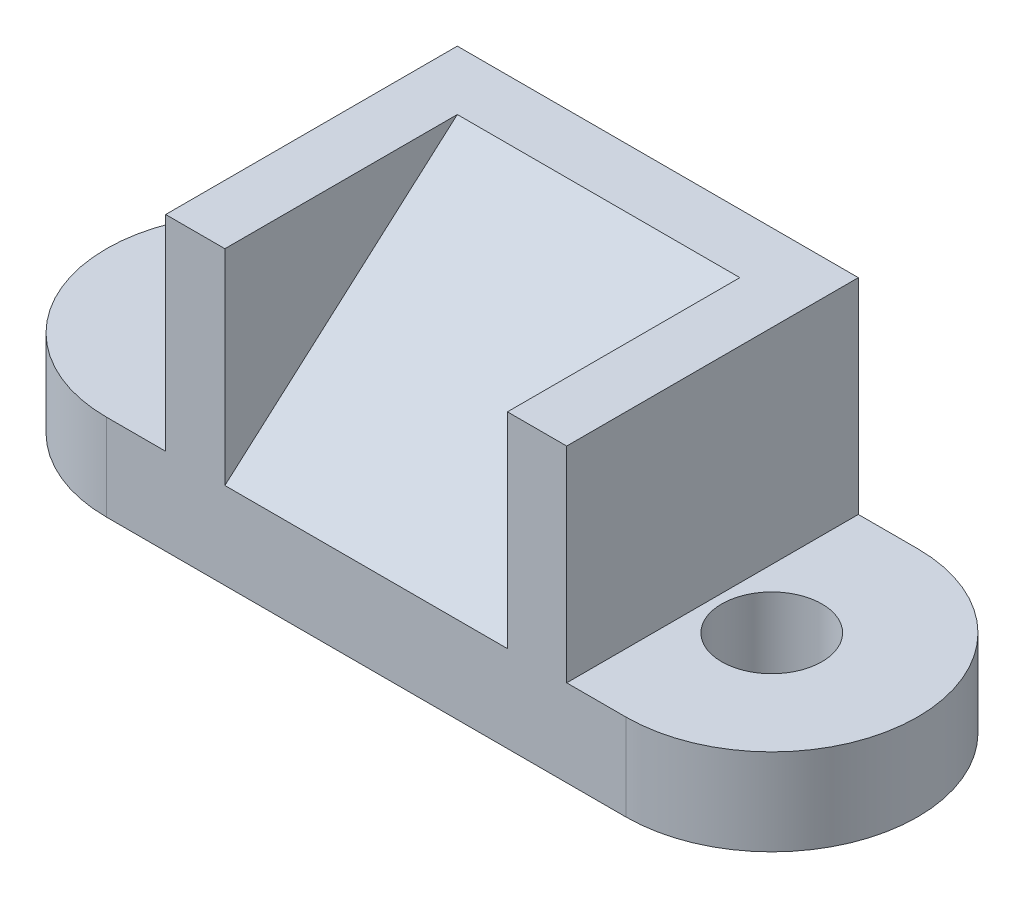
SolidWorks part; units mm, degrees
ref_plane "Front Plane" through (0, 0, 0) normal (0, 0, 1) x (1, 0, 0)
ref_plane "Top Plane" through (0, 0, 0) normal (0, 1, 0) x (1, 0, 0)
ref_plane "Right Plane" through (0, 0, 0) normal (1, 0, 0) x (0, 0, -1)
sketch "Sketch1" plane through (0, 0, 0) normal (0, 1, 0) x (1, 0, 0)
  line L2 (0, 0) -> (114, 0) construction
  line L3 (57, 0) -> (57, 46.98) construction
  line L4 (57, 0) -> (57, -55.98) construction
  line L7 (0, -32) -> (114, -32)
  line L8 (0, 32) -> (114, 32)
  arc A0 (0, 32) -> (0, -32) centre (0, 0) ccw
  arc A3 (114, 32) -> (114, -32) centre (114, 0) cw
  dimension "D1" = 64
  dimension "D3" = 114
extrude "Boss-Extrude2" add sketch "Sketch1" along normal blind 64
sketch "Sketch6" plane through (0, 64, 0) normal (0, 1, 0) x (1, 0, 0)
  line L5 (57, 46.98) -> (57, -55.98)
  line L7 (114, 32) -> (114, -32)
  line L8 (15.6619, 32) -> (93.8953, 32)
  line L9 (0, 32) -> (114, 32) construction
  line L10 (93.8953, 32) -> (93.8953, -32)
  line L11 (0, -32) -> (114, -32) construction
  line L12 (93.8953, -32) -> (15.6619, -32)
  line L13 (15.6619, -32) -> (15.6619, 32)
  line L14 (0, 32) -> (0, -32)
  circle A1 centre (0, 0) radius 11
  circle A6 centre (114, 0) radius 11
  arc A7 (0, 32) -> (0, -32) centre (0, 0) ccw
  arc A8 (0, 32) -> (0, -32) centre (0, 0) ccw construction
  arc A9 (114, -32) -> (114, 32) centre (114, 0) ccw
  arc A10 (114, -32) -> (114, 32) centre (114, 0) ccw construction
  dimension "D1" = 22
  dimension "D2" = 22
extrude "Cut-Extrude3" cut sketch "Sketch6" against normal blind 45 contours L14 A7
sketch "Sketch7" plane through (0, 64, 0) normal (0, 1, 0) x (1, 0, 0)
  circle A0 centre (0, 0) radius 11
  dimension "D1" = 22
extrude "Cut-Extrude5" cut sketch "Sketch7" against normal blind 96
sketch "Sketch8" plane through (0, 64, 0) normal (0, 1, 0) x (1, 0, 0)
  circle A0 centre (114, 0) radius 11
  dimension "D1" = 22
extrude "Cut-Extrude6" cut sketch "Sketch8" against normal blind 105
sketch "Sketch9" plane through (0, 64, 0) normal (0, 1, 0) x (1, 0, 0)
  line L0 (114, 32) -> (114, -32)
  arc A0 (114, -32) -> (114, 32) centre (114, 0) ccw
  arc A1 (114, -32) -> (114, 32) centre (114, 0) ccw construction
extrude "Cut-Extrude7" cut sketch "Sketch9" against normal blind 45
sketch "Sketch10" plane through (0, 64, 0) normal (0, 1, 0) x (1, 0, 0)
  line L0 (0, 32) -> (13, 32)
  line L1 (0, 32) -> (114, 32) construction
  line L2 (13, 32) -> (13, -32)
  line L3 (0, -32) -> (114, -32) construction
  line L8 (0, 32) -> (0, -32)
  line L9 (0, -32) -> (13, -32)
  dimension "D1" = 13
extrude "Cut-Extrude8" cut sketch "Sketch10" against normal blind 45
sketch "Sketch11" plane through (0, 64, 0) normal (0, 1, 0) x (1, 0, 0)
  line L0 (114, 32) -> (101, 32)
  line L1 (0, 32) -> (114, 32) construction
  line L2 (101, 32) -> (101, -32)
  line L3 (0, -32) -> (114, -32) construction
  line L4 (101, -32) -> (114, -32)
  line L5 (114, 32) -> (114, -32)
  dimension "D1" = 13
extrude "Cut-Extrude9" cut sketch "Sketch11" against normal blind 45 contours L5 L4 L2 L0
sketch "Sketch12" plane through (0, 64, 0) normal (0, 1, 0) x (1, 0, 0)
  line L0 (13, -32) -> (26, -32)
  line L2 (88, -32) -> (101, -32)
  line L3 (101, 32) -> (101, -32)
  line L4 (13, 32) -> (13, -32)
  line L5 (88, 19) -> (88, -32)
  line L6 (0, -32) -> (114, -32) construction
  line L7 (88, -32) -> (26, -32)
  line L8 (26, -32) -> (26, 19)
  line L9 (88, -32) -> (101, -32)
  line L10 (13, -32) -> (26, -32)
  line L11 (26, 19) -> (88, 19)
  line L12 (13, 32) -> (101, 32)
  line L13 (26, -32) -> (88, -32)
  dimension "D1" = 13
  dimension "D2" = 13
  dimension "D3" = 13
sketch "Sketch13" plane through (101, 0, 0) normal (1, 0, 0) x (0, 0, -1)
  line L0 (19, 64) -> (-32, 19)
  line L1 (-32, 64) -> (19, 64) construction
  line L2 (-32, 19) -> (-32, 64)
  line L3 (-32, 64) -> (19, 64)
sketch "Sketch14" plane through (0, 0, 32) normal (0, 0, 1) x (1, 0, 0)
  line L3 (26, 64) -> (26, 19)
  line L4 (13, 64) -> (26, 64) construction
  line L5 (87.8632, 64) -> (87.8632, 19)
  line L7 (87.8632, 19) -> (26, 19)
ref_plane "Plane1" through (57, 0, 0) normal (-1, 0, 0) x (0, 0, 1)
sketch "Sketch15" plane through (57, 0, 0) normal (-1, 0, 0) x (0, 0, 1)
  line L0 (-19, 64) -> (32, 19)
  line L4 (-19, 64) -> (32, 64)
  line L5 (32, 64) -> (32, 19)
extrude "Cut-Extrude12" cut sketch "Sketch15" against normal blind 31
sketch "Sketch16" plane through (57, 0, 0) normal (1, 0, 0) x (0, 0, -1)
  line L0 (-32, 64) -> (19, 64)
  line L1 (19, 64) -> (-32, 19)
  line L2 (-32, 19) -> (-32, 64)
extrude "Cut-Extrude13" cut sketch "Sketch16" against normal blind 31
